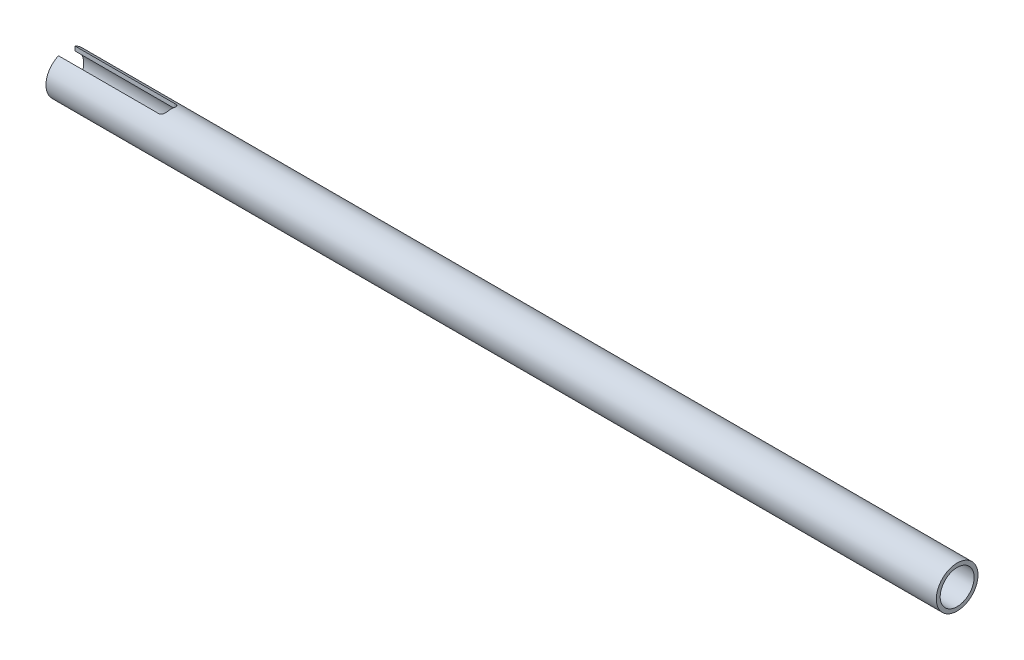
SolidWorks part; units mm, degrees
material "AISI 4130 Steel, annealed at 865C"
ref_plane "X-Y Datum" through (0, 0, 0) normal (0, 0, 1) x (1, 0, 0)
ref_plane "X-Z Datum" through (0, 0, 0) normal (0, 1, 0) x (1, 0, 0)
ref_plane "Y-Z Datum" through (0, 0, 0) normal (1, 0, 0) x (0, 0, -1)
sketch "Sketch1" plane through (0, 0, 0) normal (1, 0, 0) x (0, 0, -1)
  circle A0 centre (0, 0) radius 7.9375
  circle A1 centre (0, 0) radius 6.4643
  dimension "D1" = 15.875
  dimension "D2" = 12.9286
extrude "Boss-Extrude1" add sketch "Sketch1" along normal up to surface (192.9257 mm away) and the other way offset from surface (146.2203 mm away) 38.1 contours A0 A1
sketch "Sketch2" plane through (179.0904, 7.9375, -46.3278) normal (0, 1, 0) x (0.1149, 0, -0.9934)
  line L1 (-76.9633, 318.5793) -> (-89.8064, 317.0944) construction
  line L2 (-75.4999, 318.7485) -> (-91.2698, 316.9252) construction
  line L3 (-86.5388, 317.4722) -> (-82.1628, 279.6243)
  line L4 (-80.4035, 278.2296) -> (-77.2495, 278.5943)
  line L5 (-75.8549, 280.3536) -> (-80.2308, 318.2015)
  line L6 (-75.9539, 281.2105) -> (-79.6428, 313.1157) construction
  line L8 (-86.5388, 317.4722) -> (-80.2308, 318.2015)
  arc A0 (-77.2495, 278.5943) -> (-75.8549, 280.3536) centre (-77.4319, 280.1713) ccw
  arc A1 (-82.1628, 279.6243) -> (-80.4035, 278.2296) centre (-80.5858, 279.8066) ccw
  point P13 (-75.6725, 278.7766)
  point P16 (-81.9805, 278.0473)
  dimension "D3" = 1.5875
  dimension "D1" = 6.35
  dimension "D2" = 39.6875
extrude "Cut-Extrude1" cut sketch "Sketch2" against normal through all contours A1 L4 A0 L5 L8 L3
